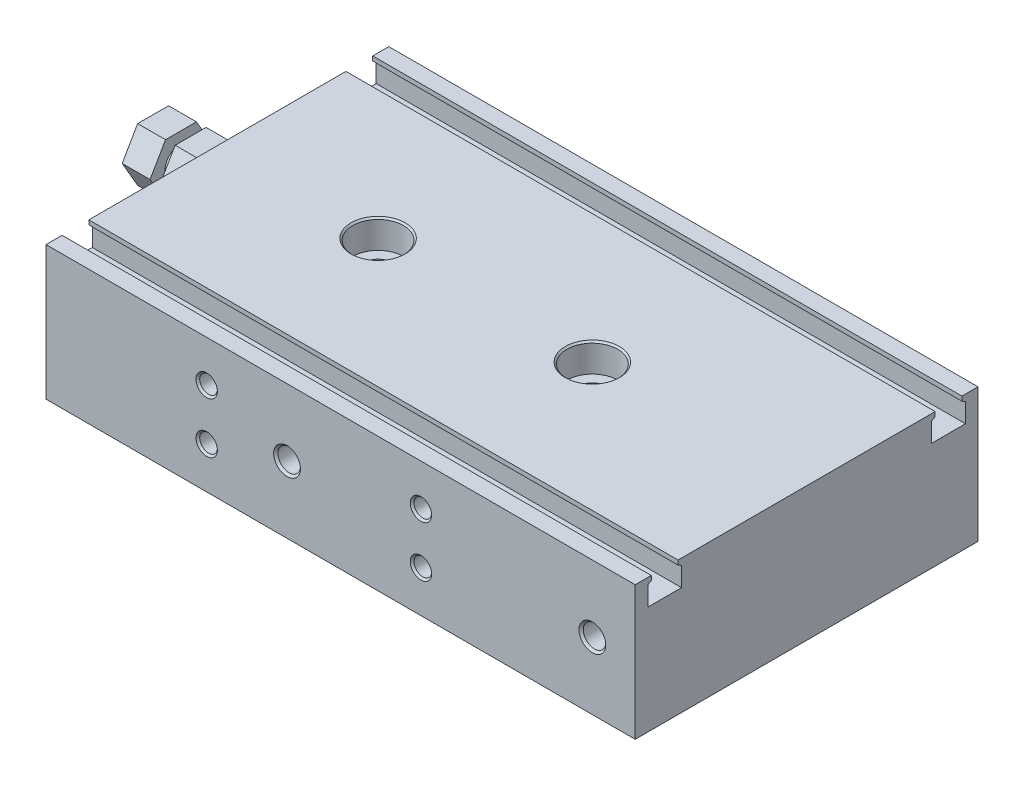
SolidWorks part; units mm, degrees
ref_plane "Plane1" through (0, 0, 0) normal (0, 0, 1) x (1, 0, 0)
ref_plane "Plane2" through (0, 0, 0) normal (0, 1, 0) x (1, 0, 0)
ref_plane "Plane3" through (0, 0, 0) normal (1, 0, 0) x (0, 0, -1)
sketch "Body_Sketch" plane through (0, 0, 0) normal (1, 0, 0) x (0, 0, -1)
  line L0 (-32, 12.5) -> (-32, -12.5)
  line L1 (-32, -12.5) -> (32, -12.5)
  line L2 (32, -12.5) -> (32, 12.5)
  line L3 (32, 12.5) -> (-32, 12.5)
  line L4 (-25.3, 0) -> (25.3, 0) construction
  line L5 (0, -7.85) -> (0, 10.85) construction
  line L6 (27.956, 0) -> (-27.956, 0) construction
  line L7 (0, 12.3416) -> (0, -12.3416) construction
  dimension "A" = 64
  dimension "B" = 25
  dimension "QQ" = 12.5
extrude "Body" add sketch "Body_Sketch" along normal blind 110
sketch "Body Bot Grooves_Sketch" [suppressed] plane through (0, 0, 0) normal (1, 0, 0) x (0, 0, -1)
  line L0 (0, 0) -> (0, -14.4793) construction
  line L1 (-12, -6.5) -> (-4, -6.5)
  line L2 (-4, -6.5) -> (-5, -5.5)
  line L3 (-5, -5.5) -> (-11, -5.5)
  line L4 (-11, -5.5) -> (-12, -6.5)
  line L5 (-8, -5.5) -> (-8, -12.5787) construction
  line L6 (18.5, 10) -> (-18.5, 10) construction
  line L7 (11, -5.5) -> (12, -6.5)
  line L8 (5, -5.5) -> (11, -5.5)
  line L9 (4, -6.5) -> (5, -5.5)
  line L10 (12, -6.5) -> (4, -6.5)
  dimension "Angle" = 45
  dimension "Raw Height" = 16.5
  dimension "Loc Y" = 15.5
  dimension "Width" = 8
  dimension "C2C" = 16
extrude "Body Bot Grooves" [suppressed] cut sketch "Body Bot Grooves_Sketch" along normal through all
sketch "Body Rod Holes_Sketch" plane through (0, 0, 0) normal (-1, 0, 0) x (0, 0, 1)
  line L0 (27.956, 0) -> (-27.956, 0) construction
  line L1 (0, 11.1009) -> (0, -8.2638) construction
  line L2 (0, -12.3416) -> (0, 12.3416) construction
  circle A0 centre (-14, 0) radius 5
  circle A1 centre (14, 0) radius 5
  dimension "NN" = 10
  dimension "H" = 28
extrude "Body Rod Holes" cut sketch "Body Rod Holes_Sketch" against normal blind 10
sketch "Body Piston Holes_Sketch" plane through (10, 0, 0) normal (-1, 0, 0) x (0, 0, 1)
  circle A0 centre (14, 0) radius 6.05
  circle A1 centre (-14, 0) radius 6.05
extrude "Body Piston Holes" cut sketch "Body Piston Holes_Sketch" against normal blind 41
sketch "Body Thru Hole_Sketch" [suppressed] plane through (0, 0, 0) normal (1, 0, 0) x (0, 0, -1)
  line L0 (0, 0) -> (0, -9.4152) construction
  line L1 (11.5, -6) -> (18.5, -6) construction
  circle A0 centre (14.95, -3) radius 1.4
  dimension "Dia" = 2.8
  dimension "Loc Y" = 3
  dimension "Loc Z" = 14.95
extrude "Body Thru Hole" [suppressed] cut sketch "Body Thru Hole_Sketch" along normal through all
sketch "Bot Switch Groove_Sketch" [suppressed] plane through (0, 0, 0) normal (1, 0, 0) x (0, 0, -1)
  line L0 (0, 0) -> (0, -12.0384) construction
  line L1 (1.6, -6.5) -> (-1.6, -6.5)
  line L2 (-1.6, -6.5) -> (-1.6, -3)
  line L3 (-1.6, -3) -> (-2.8, -3)
  line L4 (-2.8, -3) -> (-2.8, 0)
  line L5 (-2.8, 0) -> (2.8, 0)
  line L6 (2.8, -3) -> (2.8, 0)
  line L7 (-12, -6.5) -> (-4, -6.5) construction
  line L8 (1.6, -3) -> (2.8, -3)
  line L10 (1.6, -6.5) -> (1.6, -3)
  point P12 (0, 0)
  point P15 (0, -6.5)
  dimension "Bot Height" = 3.5
  dimension "Top Height" = 3
  dimension "Bot Width" = 3.2
  dimension "Top Width" = 5.6
extrude "Bot Switch Groove" [suppressed] cut sketch "Bot Switch Groove_Sketch" along normal through all
sketch "Top Switch Grooves_Sketch" plane through (0, 0, 0) normal (-1, 0, 0) x (0, 0, 1)
  line L0 (0, -12.3416) -> (0, 12.3416) construction
  line L1 (26.5, 4.6906) -> (26.5, 11.0706) construction
  line L2 (-32, 12.5) -> (32, 12.5) construction
  line L3 (23.35, 7.7) -> (29.65, 7.7)
  line L4 (-23.35, 11.3) -> (-23.35, 7.7)
  line L5 (-23.35, 7.7) -> (-29.65, 7.7)
  line L6 (-29.65, 7.7) -> (-29.65, 11.3)
  line L7 (-29, 12.5) -> (-24, 12.5)
  line L8 (29.65, 7.7) -> (29.65, 11.3)
  line L9 (29, 11.6753) -> (29.65, 11.3)
  line L10 (29, 12.5) -> (29, 11.6753)
  line L11 (29, 12.5) -> (24, 12.5)
  line L12 (-29, 12.5) -> (-29, 11.6753)
  line L13 (-24, 12.5) -> (-24, 11.6753)
  line L14 (-24, 11.6753) -> (-23.35, 11.3)
  line L15 (-29, 11.6753) -> (-29.65, 11.3)
  line L16 (0, 4.91) -> (0, 11.29) construction
  line L17 (24, 12.5) -> (24, 11.6753)
  line L18 (-26.5, 4.91) -> (-26.5, 11.29) construction
  line L19 (24, 11.6753) -> (23.35, 11.3)
  line L20 (23.35, 11.3) -> (23.35, 7.7)
  point P4 (-26.5, 12.5)
  point P12 (26.5, 12.5)
  dimension "Bot Width" = 6.3
  dimension "Top Width" = 5
  dimension "P" = 53
  dimension "Bot Height" = 3.6
  dimension "Angle" = 120
  dimension "Depth" = 4.8
extrude "Top Switch Grooves" cut sketch "Top Switch Grooves_Sketch" against normal through all
sketch "SHCS MGT Hole_Sketch" plane through (0, 0, 0) normal (0, 0, 1) x (1, 0, 0)
  line L0 (30, 12.5) -> (25.25, 12.5)
  line L1 (25.25, 12.5) -> (25.25, 7.2)
  line L2 (25.25, 7.2) -> (27.25, 7.2)
  line L3 (27.25, 7.2) -> (27.25, -12.5)
  line L4 (27.25, -12.5) -> (30, -12.5)
  line L5 (30, -12.5) -> (30, 12.5)
  line L6 (30, -11.5069) -> (30, 12.6548) construction
  line L7 (110, 12.5) -> (0, 12.5) construction
  line L8 (110, -12.5) -> (0, -12.5) construction
  line L9 (0, -12.5712) -> (0, 12.5712) construction
  dimension "M_depth" = 5.3
  dimension "M" = 9.5
  dimension "U" = 5.5
  dimension "L" = 30
revolve "SHCS MGT Hole" cut sketch "SHCS MGT Hole_Sketch" angle 360 about L6
chamfer "SHCS MGT Hole Cham" distance 0.3 1 edges at (30, 12.5, -4.75)
pattern_linear "SHCS MGT Hole Pat" count 2 spacing 40 along (1, 0, 0) of "SHCS MGT Hole", "SHCS MGT Hole Cham"
hole_wizard "SHCS MGT Hole Bot Tap" positions "SHCS MGT Hole Bot Tap Loc" profile "SHCS MGT Hole Bot Tap Profile" tap size "M4x0.7" standard "Ansi Metric"
sketch "SHCS MGT Hole Bot Tap Loc" plane through (0, -12.5, 0) normal (0, -1, 0) x (1, 0, 0)
  circle A0 centre (70, 0) radius 2.75 construction
  circle A1 centre (30, 0) radius 2.75 construction
  point P0 (30, 0)
  point P1 (70, 0)
sketch "SHCS MGT Hole Bot Tap Profile" plane through (30, -12.5, 0) normal (1, 0, 0) x (0, 0, -1)
  line L0 (0, 0) -> (0, 12.6524)
  line L1 (0, 12.6524) -> (2.75, 11)
  line L2 (2.75, 11) -> (2.75, 10)
  line L3 (2.75, 10) -> (3, 10)
  line L5 (3, 10) -> (3, 0.3)
  line L6 (3, 0.3) -> (3.3, 0)
  line L7 (3.3, 0) -> (0, 0)
  line L8 (-3, 0.3) -> (-3.3, 0) construction
  line L10 (0, 12.6524) -> (-2.75, 11) construction
  line L11 (0, -6.35) -> (0, 107.95) construction
  dimension "Tap Drill Dia." = 5.5
  dimension "Tap Drill Depth" = 11
  dimension "Thread Major Dia." = 6
  dimension "Thread Depth" = 10
  dimension "Near CSink Dia." = 6.6
  dimension "Near CSink Angle" = 90
  dimension "Drill Angle" = 118
sketch "Adjuster Nut_Sketch" plane through (0, 0, 0) normal (-1, 0, 0) x (0, 0, 1)
  line L0 (-2.8868, 11.5) -> (2.8868, 11.5)
  line L1 (2.8868, 11.5) -> (5.7735, 6.5)
  line L2 (2.8868, 1.5) -> (5.7735, 6.5)
  line L3 (2.8868, 1.5) -> (-2.8868, 1.5)
  line L4 (-5.7735, 6.5) -> (-2.8868, 1.5)
  line L5 (-2.8868, 11.5) -> (-5.7735, 6.5)
  line L6 (0, -12.3416) -> (0, 12.3416) construction
  line L7 (27.956, 0) -> (-27.956, 0) construction
  line L8 (-4.4456, 6.5) -> (4.4456, 6.5) construction
  line L10 (0, 1.15) -> (0, 8.85) construction
  circle A0 centre (0, 6.5) radius 5 construction
  dimension "OO_keyw" = 10
  dimension "TT" = 6.5
extrude "Adjuster Nut" add sketch "Adjuster Nut_Sketch" along normal blind 12
sketch "Adjuster Nut Threads_Sketch" plane through (0, 0, 0) normal (0, 0, 1) x (1, 0, 0)
  line L0 (-6.8, 34.5) -> (-6.8, 9.5)
  line L1 (-6.8, 9.5) -> (-5, 9.5)
  line L2 (-5, 9.5) -> (-5, 34.5)
  line L3 (-5, 34.5) -> (-6.8, 34.5)
  line L4 (-6.476, 6.5) -> (-3.044, 6.5) construction
  line L5 (-12, 6.5) -> (0, 6.5) construction
  line L6 (0, -12.5712) -> (0, 12.5712) construction
  line L7 (-12, 6.5) -> (-12, 11.5) construction
  line L8 (0, 12.5) -> (0, -12.5) construction
  dimension "OO" = 6
  dimension "Nut Thickness Body" = 5
  dimension "Nut Thickness Plate" = 5.2
revolve "Adjuster Nut Threads" cut sketch "Adjuster Nut Threads_Sketch" angle 360 about L4
hole_wizard "Tap Drill for M5x0.8 Tap1" positions "Sketch2" profile "Sketch1" hole size "M5x0.8" standard "ANSI Metric"
sketch "Sketch2" plane through (0, 0, 32) normal (0, 0, 1) x (1, 0, 0)
  line L0 (110, -12.5) -> (0, -12.5) construction
  line L1 (110, 12.5) -> (110, -12.5) construction
  line L2 (0, 12.5) -> (0, -12.5) construction
  point P0 (45, 0)
  point P2 (102, 0)
  dimension "D1" = 12.5
  dimension "D2" = 8
  dimension "D3" = 45
sketch "Sketch1" plane through (45, 0, 32) normal (1, 0, 0) x (0, -1, 0)
  line L0 (0, 0) -> (0, 5.7618)
  line L1 (0, 5.7618) -> (2.1, 4.5)
  line L2 (2.1, 4.5) -> (2.1, 0.4)
  line L3 (2.1, 0.4) -> (2.5, 0)
  line L5 (2.5, 0) -> (0, 0)
  line L6 (-2.1, 0.4) -> (-2.5, 0) construction
  line L10 (0, 5.7618) -> (-2.1, 4.5) construction
  line L11 (0, -6.35) -> (0, 107.95) construction
  dimension "Hole Dia." = 4.2
  dimension "Hole Depth" = 4.5
  dimension "Near C'Sink Dia." = 5
  dimension "Near C'Sink Angle" = 90
  dimension "Drill Angle" = 118
hole_wizard "Tap Drill for M5x0.8 Tap2" positions "Sketch4" profile "Sketch3" hole size "M5x0.8" standard "ANSI Metric"
sketch "Sketch4" plane through (0, 0, -32) normal (0, 0, -1) x (-1, 0, 0)
  line L0 (-110, -12.5) -> (-110, 12.5) construction
  line L1 (0, -12.5) -> (0, 12.5) construction
  line L2 (-110, -12.5) -> (0, -12.5) construction
  point P0 (-102, 0)
  point P2 (-45, 0)
  dimension "D1" = 8
  dimension "D2" = 45
  dimension "D3" = 12.5
sketch "Sketch3" plane through (102, 0, -32) normal (1, 0, 0) x (0, 1, 0)
  line L0 (0, 0) -> (0, 5.7618)
  line L1 (0, 5.7618) -> (2.1, 4.5)
  line L2 (2.1, 4.5) -> (2.1, 0.4)
  line L3 (2.1, 0.4) -> (2.5, 0)
  line L5 (2.5, 0) -> (0, 0)
  line L6 (-2.1, 0.4) -> (-2.5, 0) construction
  line L10 (0, 5.7618) -> (-2.1, 4.5) construction
  line L11 (0, -6.35) -> (0, 107.95) construction
  dimension "Hole Dia." = 4.2
  dimension "Hole Depth" = 4.5
  dimension "Near C'Sink Dia." = 5
  dimension "Near C'Sink Angle" = 90
  dimension "Drill Angle" = 118
hole_wizard "Mount_Holes_1" positions "Sketch6" profile "Sketch5" hole size "M3x0.5" standard "ANSI Metric"
sketch "Sketch6" plane through (0, 0, 32) normal (0, 0, 1) x (1, 0, 0)
  line L0 (110, -12.5) -> (0, -12.5) construction
  line L1 (0, 12.5) -> (0, -12.5) construction
  point P0 (30, -4.75)
  point P2 (70, -4.75)
  dimension "D1" = 7.75
  dimension "D2" = 30
  dimension "D3" = 40
sketch "Sketch5" plane through (30, -4.75, 32) normal (1, 0, 0) x (0, -1, 0)
  line L0 (0, 0) -> (0, 6.4914)
  line L1 (0, 6.4914) -> (1.65, 5.5)
  line L2 (1.65, 5.5) -> (1.65, 0.35)
  line L3 (1.65, 0.35) -> (2, 0)
  line L5 (2, 0) -> (0, 0)
  line L6 (-1.65, 0.35) -> (-2, 0) construction
  line L10 (0, 6.4914) -> (-1.65, 5.5) construction
  line L11 (0, -6.35) -> (0, 107.95) construction
  dimension "Hole Dia." = 3.3
  dimension "Hole Depth" = 5.5
  dimension "Near C'Sink Dia." = 4
  dimension "Near C'Sink Angle" = 90
  dimension "Drill Angle" = 118
hole_wizard "Mount_Holes_2" positions "Sketch8" profile "Sketch7" hole size "M3x0.5" standard "ANSI Metric"
sketch "Sketch8" plane through (0, 0, -32) normal (0, 0, -1) x (-1, 0, 0)
  line L0 (-110, -12.5) -> (0, -12.5) construction
  line L1 (0, -12.5) -> (0, 12.5) construction
  point P0 (-70, -4.75)
  point P2 (-30, -4.75)
  dimension "D1" = 7.75
  dimension "D2" = 30
  dimension "D3" = 40
sketch "Sketch7" plane through (70, -4.75, -32) normal (1, 0, 0) x (0, 1, 0)
  line L0 (0, 0) -> (0, 6.4914)
  line L1 (0, 6.4914) -> (1.65, 5.5)
  line L2 (1.65, 5.5) -> (1.65, 0.35)
  line L3 (1.65, 0.35) -> (2, 0)
  line L5 (2, 0) -> (0, 0)
  line L6 (-1.65, 0.35) -> (-2, 0) construction
  line L10 (0, 6.4914) -> (-1.65, 5.5) construction
  line L11 (0, -6.35) -> (0, 107.95) construction
  dimension "Hole Dia." = 3.3
  dimension "Hole Depth" = 5.5
  dimension "Near C'Sink Dia." = 4
  dimension "Near C'Sink Angle" = 90
  dimension "Drill Angle" = 118
hole_wizard "Mount_Holes_3" positions "Sketch10" profile "Sketch9" hole size "M4x0.7" standard "ANSI Metric"
sketch "Sketch10" plane through (0, 0, 32) normal (0, 0, 1) x (1, 0, 0)
  line L0 (110, 12.5) -> (0, 12.5) construction
  line L1 (0, 12.5) -> (0, -12.5) construction
  point P0 (30, 4.75)
  point P2 (70, 4.75)
  dimension "D1" = 7.75
  dimension "D2" = 30
  dimension "D3" = 40
sketch "Sketch9" plane through (30, 4.75, 32) normal (1, 0, 0) x (0, -1, 0)
  line L0 (0, 0) -> (0, 6.4914)
  line L1 (0, 6.4914) -> (1.65, 5.5)
  line L2 (1.65, 5.5) -> (1.65, 0.35)
  line L3 (1.65, 0.35) -> (2, 0)
  line L5 (2, 0) -> (0, 0)
  line L6 (-1.65, 0.35) -> (-2, 0) construction
  line L10 (0, 6.4914) -> (-1.65, 5.5) construction
  line L11 (0, -6.35) -> (0, 107.95) construction
  dimension "Hole Dia." = 3.3
  dimension "Hole Depth" = 5.5
  dimension "Near C'Sink Dia." = 4
  dimension "Near C'Sink Angle" = 90
  dimension "Drill Angle" = 118
hole_wizard "Mount_Holes_4" positions "Sketch12" profile "Sketch11" hole size "M4x0.7" standard "ANSI Metric"
sketch "Sketch12" plane through (0, 0, -32) normal (0, 0, -1) x (-1, 0, 0)
  line L1 (-110, 12.5) -> (0, 12.5) construction
  line L2 (0, -12.5) -> (0, 12.5) construction
  point P0 (-70, 4.75)
  point P2 (-30, 4.75)
  dimension "D1" = 7.75
  dimension "D2" = 30
  dimension "D3" = 40
sketch "Sketch11" plane through (70, 4.75, -32) normal (1, 0, 0) x (0, 1, 0)
  line L0 (0, 0) -> (0, 6.4914)
  line L1 (0, 6.4914) -> (1.65, 5.5)
  line L2 (1.65, 5.5) -> (1.65, 0.35)
  line L3 (1.65, 0.35) -> (2, 0)
  line L5 (2, 0) -> (0, 0)
  line L6 (-1.65, 0.35) -> (-2, 0) construction
  line L10 (0, 6.4914) -> (-1.65, 5.5) construction
  line L11 (0, -6.35) -> (0, 107.95) construction
  dimension "Hole Dia." = 3.3
  dimension "Hole Depth" = 5.5
  dimension "Near C'Sink Dia." = 4
  dimension "Near C'Sink Angle" = 90
  dimension "Drill Angle" = 118
hole_wizard "1/8 Rc Tapped Hole1" [suppressed] positions "Sketch14" profile "Sketch13" size "1/8" standard "ISO"
sketch "Sketch14" plane through (0, 0, 49) normal (0, 0, 1) x (1, 0, 0)
  line L0 (182, -19) -> (0, -19) construction
  line L1 (0, 19) -> (0, -19) construction
  line L2 (182, 19) -> (182, -19) construction
  point P0 (56, 0)
  point P2 (172, 0)
  dimension "D1" = 15
  dimension "D2" = 46
  dimension "D3" = 9
sketch "Sketch13" plane through (56, 0, 49) normal (1, 0, 0) x (0, -1, 0)
  line L0 (0, 0) -> (0, 11.4134)
  line L1 (3.95, 9.04) -> (0, 11.4134)
  line L2 (-3.95, 9.04) -> (0, 11.4134) construction
  line L3 (3.95, 9.04) -> (3.95, 4.5)
  line L4 (3.95, 4.5) -> (4.633, 4.5)
  line L5 (4.633, 4.5) -> (4.7735, 0)
  line L6 (-4.633, 4.5) -> (-4.7735, 0) construction
  line L7 (4.7735, 0) -> (0, 0)
  line L8 (0, -6.35) -> (0, 107.95) construction
  line L11 (-3.95, 4.5) -> (-4.633, 4.5) construction
  dimension "Tap Drill Dia." = 7.9
  dimension "Tap Drill Depth" = 9.04
  dimension "Thread Dia." = 9.5469
  dimension "Thread Angle" = 3.576
  dimension "Thread Depth" = 4.5
  dimension "Drill Angle" = 118
hole_wizard "1/8 Rc Tapped Hole2" [suppressed] positions "Sketch16" profile "Sketch15" size "1/8" standard "ISO"
sketch "Sketch16" plane through (0, 0, -49) normal (0, 0, -1) x (-1, 0, 0)
  line L0 (-182, -19) -> (0, -19) construction
  line L1 (0, -19) -> (0, 19) construction
  line L2 (-182, -19) -> (-182, 19) construction
  point P0 (-172, 0)
  point P2 (-56, 0)
  dimension "D1" = 15
  dimension "D2" = 46
  dimension "D3" = 9
sketch "Sketch15" plane through (172, 0, -49) normal (1, 0, 0) x (0, 1, 0)
  line L0 (0, 0) -> (0, 11.4134)
  line L1 (3.95, 9.04) -> (0, 11.4134)
  line L2 (-3.95, 9.04) -> (0, 11.4134) construction
  line L3 (3.95, 9.04) -> (3.95, 4.5)
  line L4 (3.95, 4.5) -> (4.633, 4.5)
  line L5 (4.633, 4.5) -> (4.7735, 0)
  line L6 (-4.633, 4.5) -> (-4.7735, 0) construction
  line L7 (4.7735, 0) -> (0, 0)
  line L8 (0, -6.35) -> (0, 107.95) construction
  line L11 (-3.95, 4.5) -> (-4.633, 4.5) construction
  dimension "Tap Drill Dia." = 7.9
  dimension "Tap Drill Depth" = 9.04
  dimension "Thread Dia." = 9.5469
  dimension "Thread Angle" = 3.576
  dimension "Thread Depth" = 4.5
  dimension "Drill Angle" = 118
